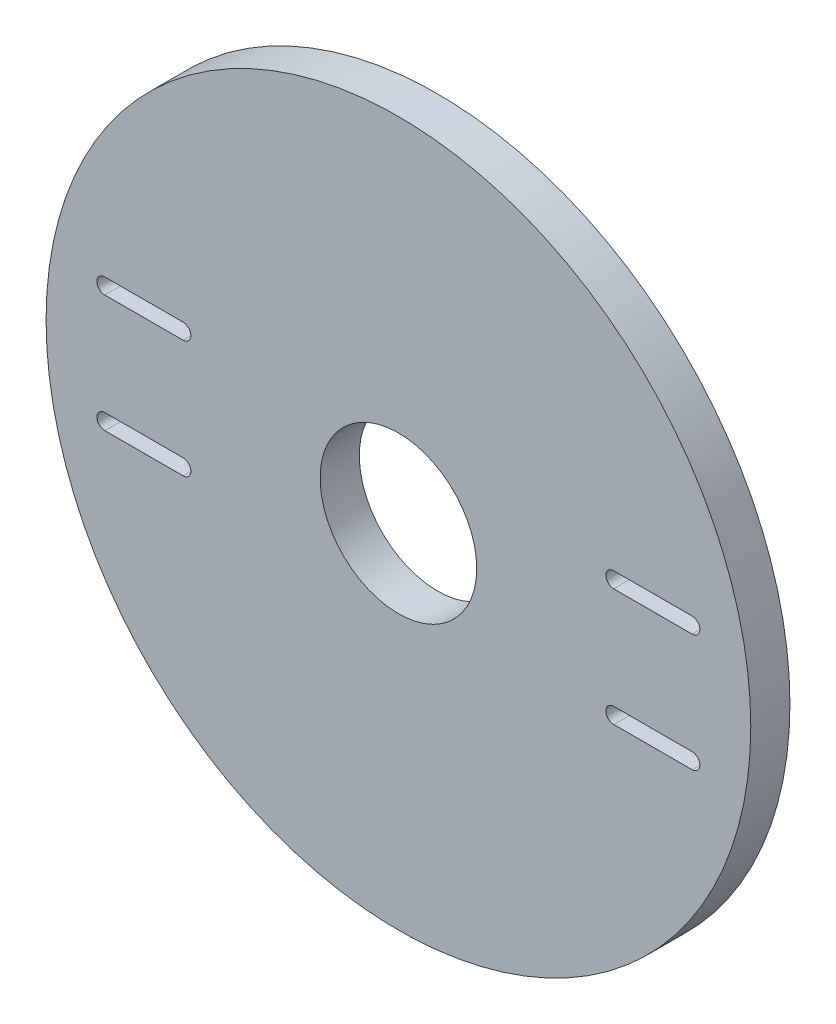
SolidWorks part; units mm, degrees
ref_plane "前视基准面" through (0, 0, 0) normal (0, 0, 1) x (1, 0, 0)
ref_plane "上视基准面" through (0, 0, 0) normal (0, 1, 0) x (1, 0, 0)
ref_plane "右视基准面" through (0, 0, 0) normal (1, 0, 0) x (0, 0, -1)
sketch "草图1" plane through (0, 0, 0) normal (0, 0, 1) x (1, 0, 0)
  circle A0 centre (0, 0) radius 180
  dimension "D1" = 360
extrude "凸台-拉伸1" add sketch "草图1" along normal blind 20
sketch "草图2" plane through (0, 0, 20) normal (0, 0, 1) x (1, 0, 0)
  line L0 (0, 0) -> (-42.4271, 0) construction
  line L1 (0, 0) -> (0, 21.6347) construction
  line L2 (-110, 30) -> (-150, 30) construction
  line L3 (0, -30) -> (0, 0) construction
  line L4 (0, -30) -> (-110, -30) construction
  line L5 (-110, 34) -> (-150, 34)
  line L6 (-110, -30) -> (-150, -30) construction
  line L7 (-110, -34) -> (-150, -34)
  line L8 (-110, -26) -> (-150, -26)
  line L9 (-110, 26) -> (-150, 26)
  line L10 (110, 30) -> (150, 30) construction
  line L11 (110, 34) -> (150, 34)
  line L12 (110, 26) -> (150, 26)
  line L13 (110, -30) -> (150, -30) construction
  line L14 (110, -34) -> (150, -34)
  line L15 (110, -26) -> (150, -26)
  arc A0 (-110, 34) -> (-110, 26) centre (-110, 30) cw
  arc A1 (-150, 26) -> (-150, 34) centre (-150, 30) cw
  arc A2 (-110, -34) -> (-110, -26) centre (-110, -30) ccw
  arc A3 (-150, -26) -> (-150, -34) centre (-150, -30) ccw
  arc A4 (110, 34) -> (110, 26) centre (110, 30) ccw
  arc A5 (150, 26) -> (150, 34) centre (150, 30) ccw
  arc A6 (110, -34) -> (110, -26) centre (110, -30) cw
  arc A7 (150, -26) -> (150, -34) centre (150, -30) cw
  point P7 (-130, -30)
  point P9 (-130, 30)
  point P22 (130, 30)
  point P29 (130, -30)
  dimension "D5" = 40
  dimension "D8" = 4
  dimension "D6" = 110
  dimension "D7" = 30
sketch "草图3" plane through (0, 0, 20) normal (0, 0, 1) x (1, 0, 0)
  circle A0 centre (0, 0) radius 40
  dimension "D1" = 80
extrude "切除-拉伸2" cut sketch "草图3" against normal blind 254
extrude "切除-拉伸3" cut sketch "草图2" against normal up to next
